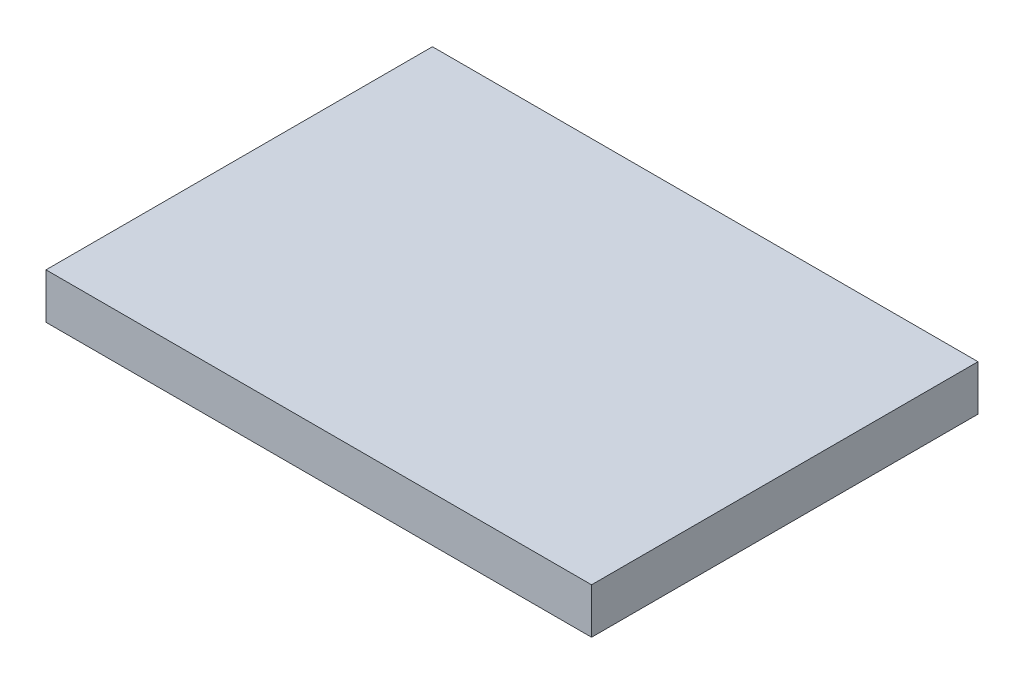
SolidWorks part; units mm, degrees
ref_plane "Front Plane" through (0, 0, 0) normal (0, 0, 1) x (1, 0, 0)
ref_plane "Top Plane" through (0, 0, 0) normal (0, 1, 0) x (1, 0, 0)
ref_plane "Right Plane" through (0, 0, 0) normal (1, 0, 0) x (0, 0, -1)
sketch "Sketch1" plane through (0, 0, 0) normal (0, 1, 0) x (1, 0, 0)
  line L1 (0, 0) -> (30.48, 0)
  line L2 (0, 0) -> (0, 21.59)
  line L3 (0, 21.59) -> (30.48, 21.59)
  line L4 (30.48, 0) -> (30.48, 21.59)
  dimension "D1" = 30.48
  dimension "D2" = 21.59
extrude "Boss-Extrude1" add sketch "Sketch1" along normal blind 2.54
